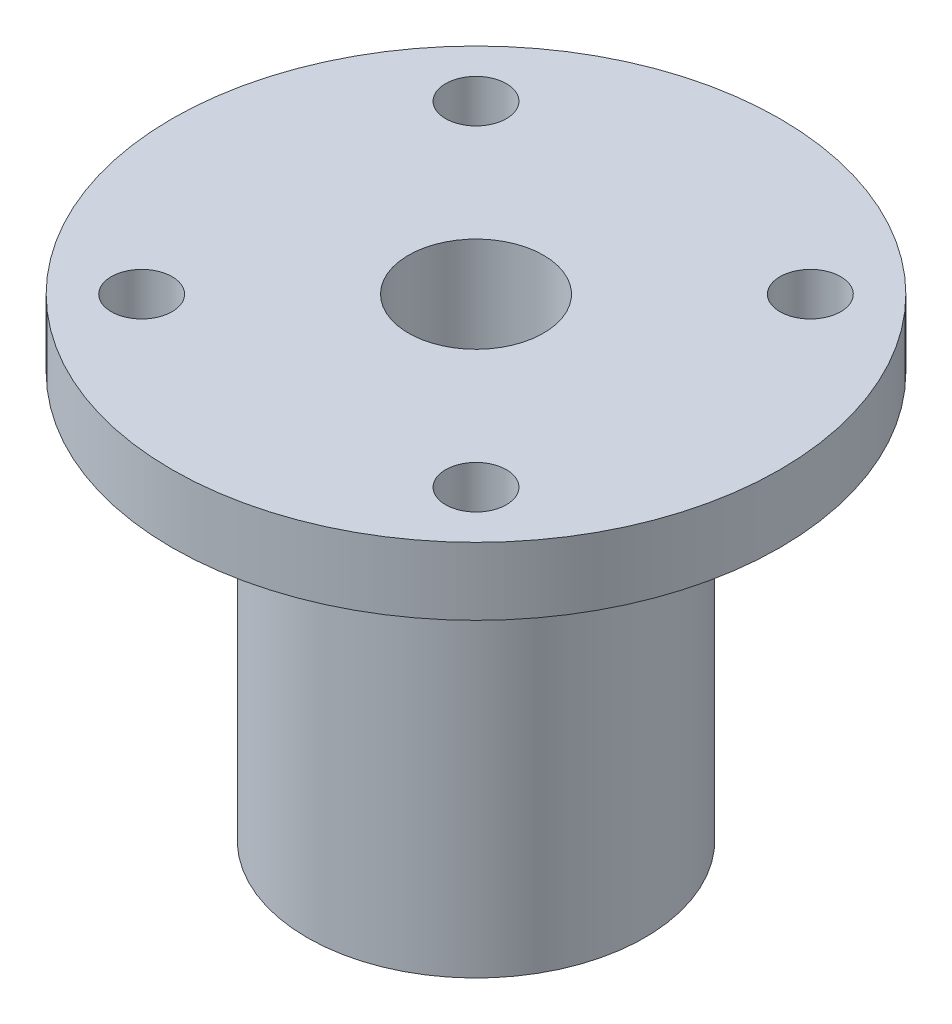
SolidWorks part; units mm, degrees
ref_plane "Спереди" through (0, 0, 0) normal (0, 0, 1) x (1, 0, 0)
ref_plane "Сверху" through (0, 0, 0) normal (0, 1, 0) x (1, 0, 0)
ref_plane "Справа" through (0, 0, 0) normal (1, 0, 0) x (0, 0, -1)
sketch "Эскиз1" plane through (0, 0, 0) normal (0, 0, 1) x (1, 0, 0)
  line L0 (0, 0) -> (0, 64.4843) construction
  line L1 (5, 35) -> (22.5, 35)
  line L2 (22.5, 35) -> (22.5, 30)
  line L3 (22.5, 30) -> (12.5, 30)
  line L4 (12.5, 30) -> (12.5, 0)
  line L5 (12.5, 0) -> (5, 0)
  line L6 (5, 0) -> (5, 35)
  dimension "D1" = 10
  dimension "D2" = 25
  dimension "D3" = 30
  dimension "D4" = 35
  dimension "D5" = 45
revolve "Повернуть1" add sketch "Эскиз1" angle 360 about L0
hole_wizard "Отверстие с зазором M41" positions "Эскиз3" profile "Эскиз4" hole size "M4" standard "DIN" end condition through all
sketch "Эскиз3" plane through (0, 30, 0) normal (0, -1, 0) x (1, 0, 0)
  line L1 (-12.3744, 12.3744) -> (12.3744, 12.3744)
  line L2 (-12.3744, 12.3744) -> (-12.3744, -12.3744)
  line L3 (-12.3744, -12.3744) -> (12.3744, -12.3744)
  line L4 (12.3744, 12.3744) -> (12.3744, -12.3744)
  circle A0 centre (0, 0) radius 17.5
  point P0 (-12.3744, 12.3744)
  point P54 (-12.3744, -12.3744)
  point P56 (12.3744, -12.3744)
  point P58 (12.3744, 12.3744)
  dimension "D1" = 35
sketch "Эскиз4" plane through (-12.3744, 30, 12.3744) normal (1, 0, 0) x (0, 0, -1)
  line L0 (0, 0) -> (0, 5)
  line L1 (0, 5) -> (2.25, 5)
  line L2 (2.25, 5) -> (2.25, 0)
  line L5 (2.25, 0) -> (0, 0)
  line L11 (0, -6.35) -> (0, 107.95) construction
  dimension "Диаметр сквозного отверстия" = 4.5
  dimension "Глубина сквозного отверстия" = 5
